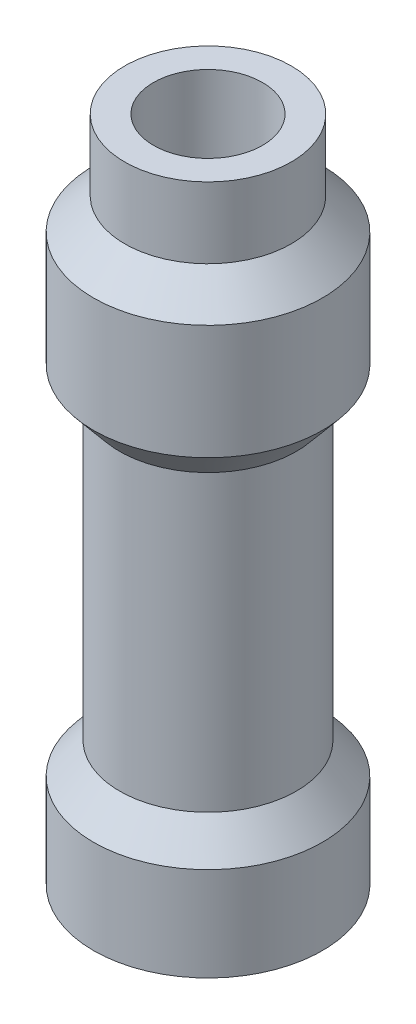
SolidWorks part; units mm, degrees
ref_plane "Piano frontale" through (0, 0, 0) normal (0, 0, 1) x (1, 0, 0)
ref_plane "Piano superiore" through (0, 0, 0) normal (0, 1, 0) x (1, 0, 0)
ref_plane "Piano destro" through (0, 0, 0) normal (1, 0, 0) x (0, 0, -1)
sketch "Schizzo1" plane through (0, 0, 0) normal (0, 0, 1) x (1, 0, 0)
  line L0 (0, 0) -> (0, 46.4574) construction
  line L1 (0, 0) -> (5.49, 0)
  line L2 (5.49, 0) -> (5.49, 4.5)
  line L3 (5.49, 4.5) -> (4.24, 6)
  line L4 (4.24, 6) -> (4.24, 20.11)
  line L5 (4.24, 20.11) -> (5.49, 21.61)
  line L6 (5.49, 21.61) -> (5.49, 27.11)
  line L7 (5.49, 27.11) -> (3.995, 28.61)
  line L8 (3.995, 28.61) -> (3.995, 32.01)
  line L9 (3.995, 32.01) -> (2.615, 32.01)
  line L10 (2.615, 32.01) -> (2.615, 7.08)
  line L11 (2.615, 7.08) -> (0, 7.08)
  line L12 (0, 0) -> (0, 7.08)
  dimension "D1" = 32.01
  dimension "D2" = 10.98
  dimension "D3" = 10.98
  dimension "D4" = 5.23
  dimension "D5" = 7.99
  dimension "D6" = 8.48
  dimension "D7" = 24.93
  dimension "D8" = 1.5
  dimension "D9" = 1.5
  dimension "D10" = 1.5
  dimension "D11" = 5.5
  dimension "D12" = 4.5
  dimension "D13" = 3.4
revolve "Rivoluzione1" add sketch "Schizzo1" angle 360 about L0
hole_wizard "Foro filettato M3.5x0.6-1" positions "Schizzo3" profile "Schizzo2" tap size "M3.5x0.6" standard "Ansi Metric" end condition up to next
sketch "Schizzo3" plane through (0, 0, 0) normal (0, -1, 0) x (-1, 0, 0)
  point P0 (0, 0)
cosmetic thread "Filettatura del foro1" parameters "D2"=3.5
sketch "Schizzo2" plane through (0, 0, 0) normal (1, 0, 0) x (0, 0, -1)
  line L0 (0, 0) -> (0, 7.08)
  line L1 (0, 7.08) -> (1.45, 7.08)
  line L2 (1.45, 7.08) -> (1.45, 0)
  line L5 (1.45, 0) -> (0, 0)
  line L11 (0, -6.35) -> (0, 107.95) construction
  dimension "Thru Tap Drill Dia." = 2.9
  dimension "Thru Tap Drill Depth" = 7.08
ref_plane "Piano1" through (0, 0, -5.49) normal (0, 0, -1) x (-1, 0, 0)
hole_wizard "Foro filettato M3x0.5-2" positions "Schizzo5" profile "Schizzo4" tap size "M3x0.5" standard "Ansi Metric"
sketch "Schizzo5" plane through (0, 0, -5.49) normal (0, 0, -1) x (-1, 0, 0)
  line L0 (-5.49, 27.11) -> (5.49, 21.61) construction
  line L2 (-5.49, 21.61) -> (5.49, 27.11) construction
  point P0 (0, 24.36)
  point P16 (0, 24.36)
sketch "Schizzo4" plane through (0, 24.36, -5.49) normal (1, 0, 0) x (0, 1, 0)
  line L0 (0, 0) -> (0, 10.98)
  line L1 (0, 10.98) -> (1.25, 10.98)
  line L2 (1.25, 10.98) -> (1.25, 0)
  line L5 (1.25, 0) -> (0, 0)
  line L11 (0, -6.35) -> (0, 107.95) construction
  dimension "Thru Tap Drill Dia." = 2.5
  dimension "Thru Tap Drill Depth" = 10.98
cosmetic thread "Filettatura del foro2" parameters "D2"=3
